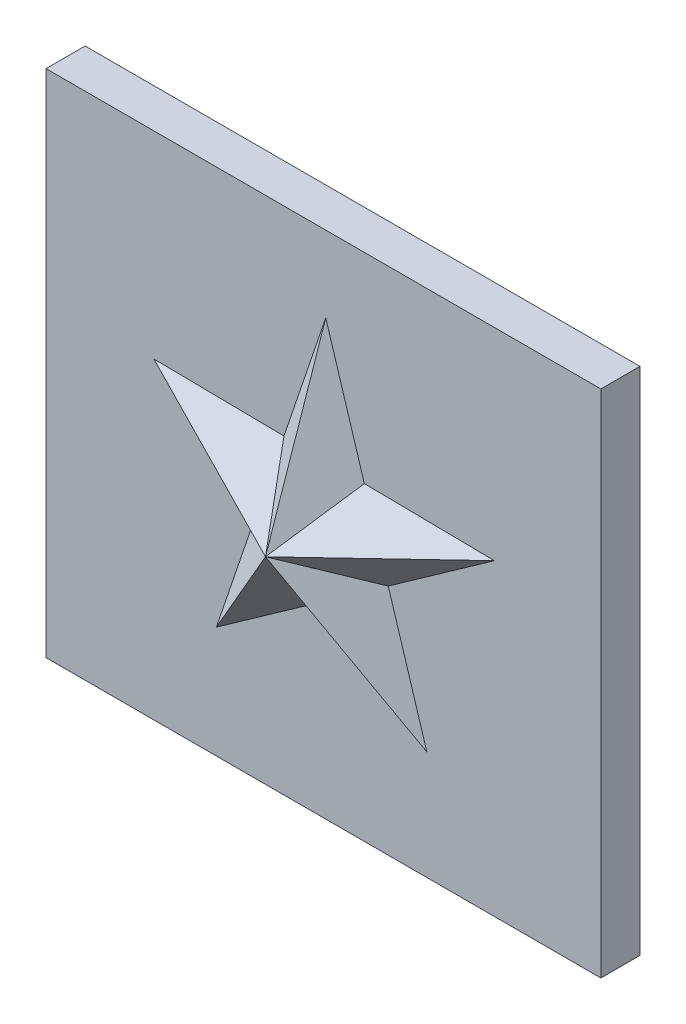
SolidWorks part; units mm, degrees
ref_plane "Front Plane" through (0, 0, 0) normal (0, 0, 1) x (1, 0, 0)
ref_plane "Top Plane" through (0, 0, 0) normal (0, 1, 0) x (1, 0, 0)
ref_plane "Right Plane" through (0, 0, 0) normal (1, 0, 0) x (0, 0, -1)
sketch "Sketch2" plane through (0, 0, 0) normal (0, 0, 1) x (1, 0, 0)
  line L0 (0.7988, 61.7982) -> (-13.6277, 19.2761)
  line L6 (-58.5268, 19.8564) -> (-22.5438, -7.0041)
  line L7 (59.0205, 18.337) -> (22.3552, -7.5845)
  line L8 (35.6778, -50.4654) -> (22.3552, -7.5845)
  line L9 (-58.5268, 19.8564) -> (-13.6277, 19.2761)
  line L10 (14.1214, 18.9174) -> (59.0205, 18.337)
  line L11 (14.1214, 18.9174) -> (0.7988, 61.7982)
  line L12 (-0.3051, -23.6048) -> (-36.9703, -49.5263)
  line L13 (-22.5438, -7.0041) -> (-36.9703, -49.5263)
  line L14 (-0.3051, -23.6048) -> (35.6778, -50.4654)
ref_plane "Plane2" through (0, 0, 20) normal (0, 0, 1) x (1, 0, 0)
sketch "Sketch4" plane through (0, 0, 20) normal (0, 0, 1) x (1, 0, 0)
  point P0 (0, 0)
loft "Loft1" add profiles "Sketch2", "Sketch4"
scale "Scale1" bodies to scale 101 scale about origin uniform scaling yes scale factor 0.222222
sketch "Sketch5" plane through (0, 0, 0) normal (0, 0, -1) x (-1, 0, 0)
  line L0 (0, 0) -> (0, 19.56) construction
  line L1 (0, 19.56) -> (0, 0) construction
  line L2 (0, 0) -> (0, -19.56) construction
  line L3 (0, -19.56) -> (-21.275, -19.56) construction
  line L4 (-21.275, -19.56) -> (-21.275, 19.56) construction
  line L5 (-21.275, 19.56) -> (21.275, 19.56) construction
  line L6 (21.275, 19.56) -> (21.275, -19.56) construction
  line L7 (21.275, -19.56) -> (0, -19.56) construction
  line L8 (21.275, 19.56) -> (21.275, -19.56)
  line L9 (21.275, -19.56) -> (-21.275, -19.56)
  line L10 (-21.275, -19.56) -> (-21.275, 19.56)
  line L11 (-21.275, 19.56) -> (21.275, 19.56)
extrude "Boss-Extrude1" add sketch "Sketch5" along normal blind 3
